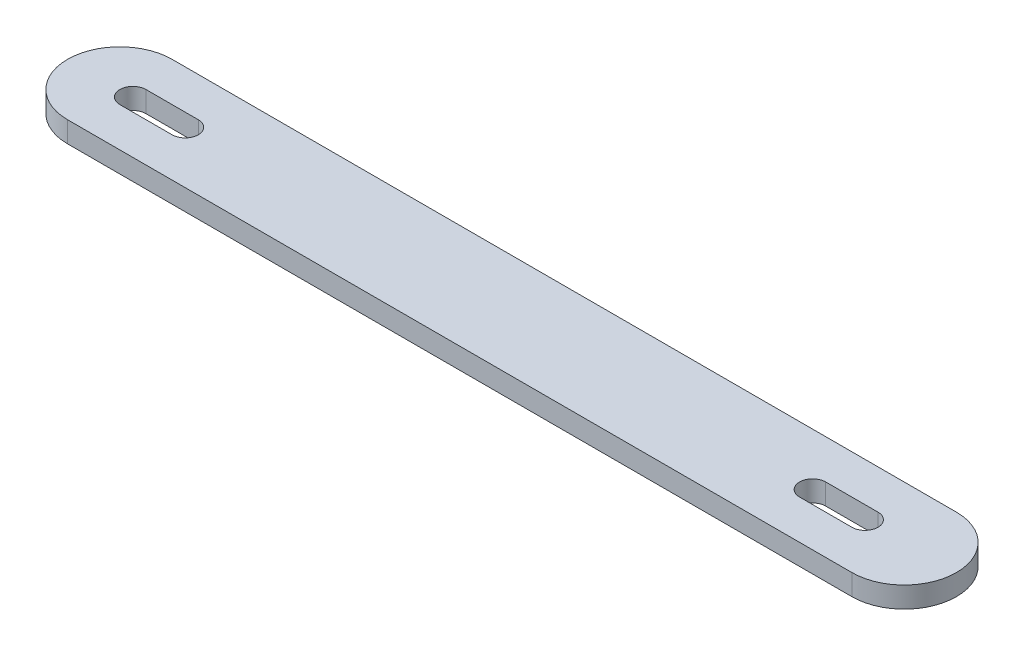
SolidWorks part; units mm, degrees
ref_plane "Front Plane" through (0, 0, 0) normal (0, 0, 1) x (1, 0, 0)
ref_plane "Top Plane" through (0, 0, 0) normal (0, 1, 0) x (1, 0, 0)
ref_plane "Right Plane" through (0, 0, 0) normal (1, 0, 0) x (0, 0, -1)
sketch "Sketch1" plane through (0, 0, 0) normal (0, 1, 0) x (1, 0, 0)
  line L0 (-75, 0) -> (75, 0) construction
  line L1 (-75, 10) -> (75, 10)
  line L2 (-75, -10) -> (75, -10)
  line L3 (-67.5, 0) -> (62.5, 0) construction
  line L4 (-72.5, 0) -> (-62.5, 0) construction
  line L5 (-72.5, 2.5) -> (-62.5, 2.5)
  line L6 (-72.5, -2.5) -> (-62.5, -2.5)
  line L7 (67.5, 0) -> (57.5, 0) construction
  line L8 (67.5, -2.5) -> (57.5, -2.5)
  line L9 (67.5, 2.5) -> (57.5, 2.5)
  arc A0 (-75, 10) -> (-75, -10) centre (-75, 0) ccw
  arc A1 (75, -10) -> (75, 10) centre (75, 0) ccw
  arc A6 (-72.5, 2.5) -> (-72.5, -2.5) centre (-72.5, 0) ccw
  arc A7 (-62.5, -2.5) -> (-62.5, 2.5) centre (-62.5, 0) ccw
  arc A8 (67.5, -2.5) -> (67.5, 2.5) centre (67.5, 0) ccw
  arc A9 (57.5, 2.5) -> (57.5, -2.5) centre (57.5, 0) ccw
  point P3 (0, 0)
  point P12 (-67.5, 0)
  point P19 (62.5, 0)
  dimension "D1" = 10
  dimension "D3" = 2.5
  dimension "D4" = 10
  dimension "D5" = 10
  dimension "D6" = 2.5
  dimension "D2" = 150
  dimension "D7" = 130
  dimension "D8" = 67.5
extrude "Boss-Extrude1" add sketch "Sketch1" along normal blind 4
